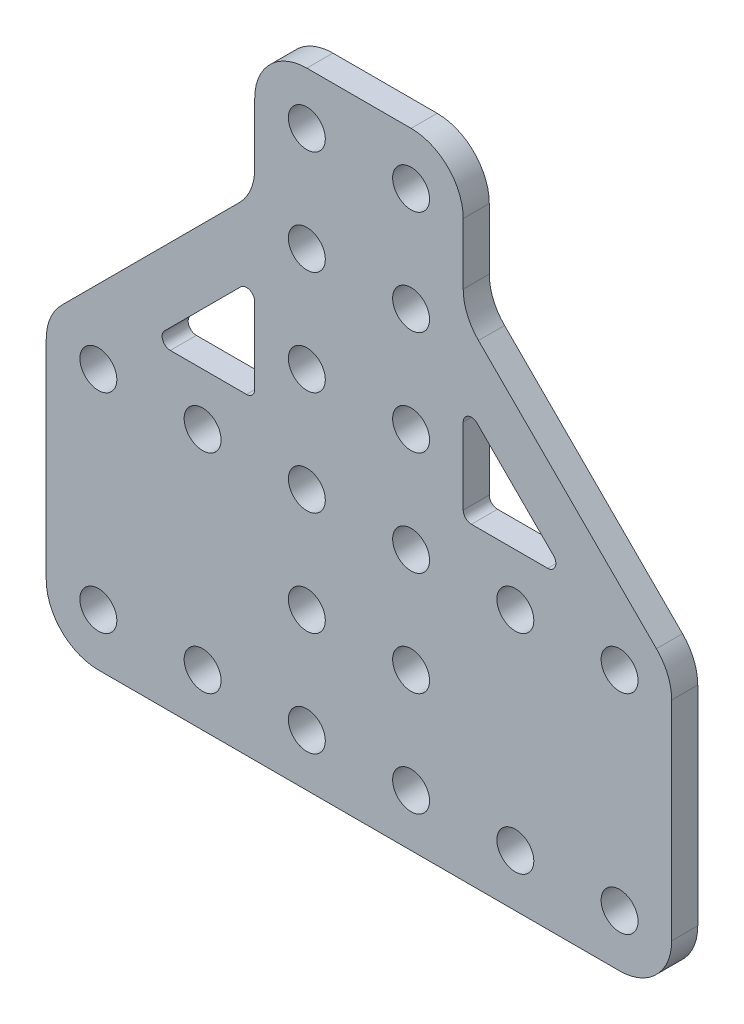
SolidWorks part; units mm, degrees
ref_plane "Front Plane" through (0, 0, 0) normal (0, 0, 1) x (1, 0, 0)
ref_plane "Top Plane" through (0, 0, 0) normal (0, 1, 0) x (1, 0, 0)
ref_plane "Right Plane" through (0, 0, 0) normal (1, 0, 0) x (0, 0, -1)
sketch "Sketch1" plane through (0, 0, 0) normal (0, 0, 1) x (1, 0, 0)
  line L1 (0, 0) -> (-76.2, 0)
  line L16 (-69.85, 31.75) -> (-44.45, 57.15) construction
  line L17 (-31.75, 57.15) -> (-6.35, 31.75) construction
  line L18 (-31.75, 57.15) -> (-44.45, 57.15) construction
  line L19 (-76.2, 0) -> (-76.2, 34.3803)
  line L20 (0, 0) -> (0, 34.3803)
  line L21 (0, 34.3803) -> (-25.4, 59.7803)
  line L23 (-50.8, 59.7803) -> (-76.2, 34.3803)
  line L24 (-63.5, 38.1) -> (-50.8, 50.8)
  line L25 (-50.8, 50.8) -> (-50.8, 38.1)
  line L26 (-50.8, 38.1) -> (-63.5, 38.1)
  line L27 (-38.1, 63.5) -> (-38.1, 57.15) construction
  line L28 (-25.4, 50.8) -> (-25.4, 38.1)
  line L29 (-12.7, 38.1) -> (-25.4, 50.8)
  line L30 (-25.4, 38.1) -> (-12.7, 38.1)
  line L33 (-50.8, 59.7803) -> (-50.8, 76.2)
  line L34 (-50.8, 76.2) -> (-25.4, 76.2)
  line L35 (-25.4, 59.7803) -> (-25.4, 76.2)
  circle A0 centre (-44.45, 57.15) radius 2.25
  circle A1 centre (-69.85, 6.35) radius 2.25
  circle A2 centre (-6.35, 6.35) radius 2.25
  circle A4 centre (-31.75, 44.45) radius 2.25
  circle A5 centre (-44.45, 44.45) radius 2.25
  circle A6 centre (-57.15, 6.35) radius 2.25
  circle A7 centre (-57.15, 31.75) radius 2.25
  circle A8 centre (-69.85, 31.75) radius 2.25
  circle A9 centre (-19.05, 6.35) radius 2.25
  circle A10 centre (-19.05, 31.75) radius 2.25
  circle A11 centre (-6.35, 31.75) radius 2.25
  circle A12 centre (-44.45, 31.75) radius 2.25
  circle A13 centre (-31.75, 31.75) radius 2.25
  circle A14 centre (-44.45, 19.05) radius 2.25
  circle A15 centre (-31.75, 19.05) radius 2.25
  circle A16 centre (-44.45, 6.35) radius 2.25
  circle A17 centre (-31.75, 6.35) radius 2.25
  circle A20 centre (-31.75, 57.15) radius 2.25
  circle A21 centre (-31.75, 69.85) radius 2.25
  circle A22 centre (-44.45, 69.85) radius 2.25
  circle A23 centre (-31.75, 57.15) radius 2.25 [skipped]
  dimension "D6" = 4.5
  dimension "D9" = 6.35
  dimension "D11" = 6.35
  dimension "D21" = 6.35
  dimension "D1" = 76.2
  dimension "D2" = 6.35
  dimension "D3" = 6.35
  dimension "D4" = 45
  dimension "D5" = 45
  dimension "D7" = 12.7
  dimension "D8" = 12.7
  dimension "D10" = 6.35
  dimension "D19" = 25.4
  dimension "D23" = 6.35
  dimension "D24" = 6.35
  dimension "D13" = 2
  dimension "D14" = 5
  dimension "D15" = 2
  dimension "D16" = 2
  dimension "D17" = 2
  dimension "D18" = 2
  dimension "D26" = 2
  dimension "D27" = 2
extrude "Boss-Extrude1" add sketch "Sketch1" along normal blind 3.175
fillet "Fillet1" radius 6.35 8 edges at (-76.2, 0, 1.5875) (0, 0, 1.5875) (0, 34.3803, 1.5875) (-76.2, 34.3803, 1.5875) (-25.4, 59.7803, 1.5875) (-25.4, 76.2, 1.5875) (-50.8, 76.2, 1.5875) (-50.8, 59.7803, 1.5875)
fillet "Fillet2" radius 1 6 edges at (-12.7, 38.1, 1.5875) (-25.4, 50.8, 1.5875) (-25.4, 38.1, 1.5875) (-50.8, 38.1, 1.5875) (-63.5, 38.1, 1.5875) (-50.8, 50.8, 1.5875)
